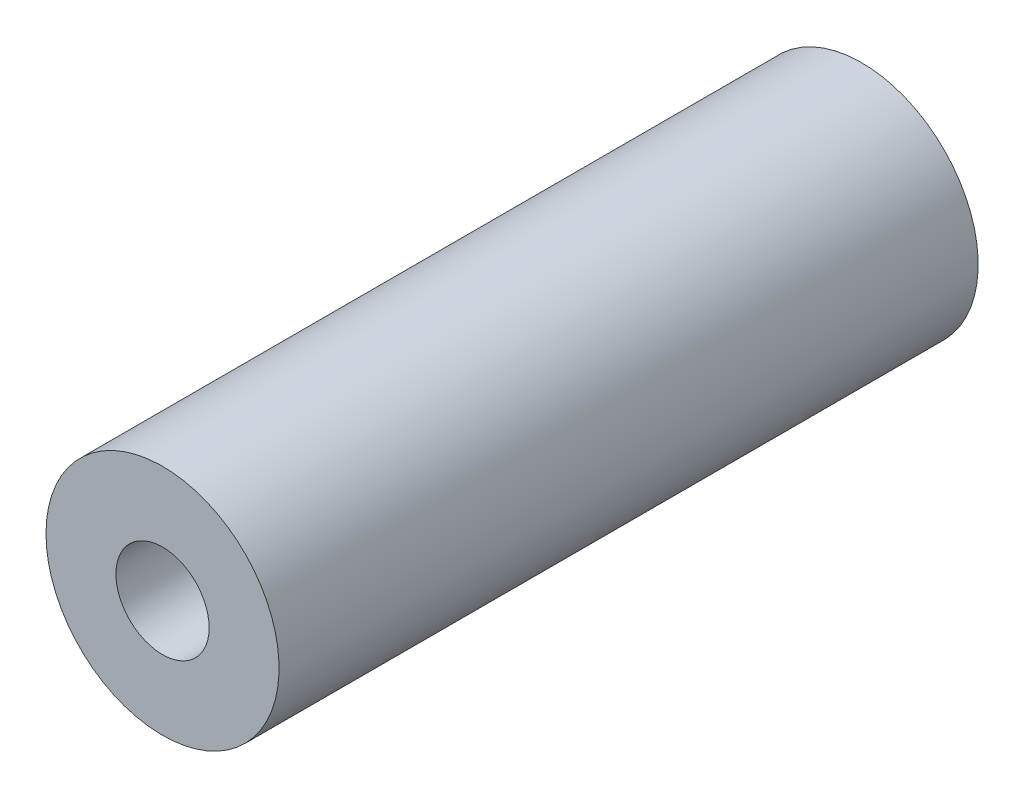
SolidWorks part; units mm, degrees
ref_plane "Front Plane" through (0, 0, 0) normal (0, 0, 1) x (1, 0, 0)
ref_plane "Top Plane" through (0, 0, 0) normal (0, 1, 0) x (1, 0, 0)
ref_plane "Right Plane" through (0, 0, 0) normal (1, 0, 0) x (0, 0, -1)
sketch "Sketch1" plane through (0, 0, 0) normal (0, 0, 1) x (1, 0, 0)
  circle A0 centre (0, 0) radius 12.7
extrude "Boss-Extrude1" add sketch "Sketch1" along normal blind 76.2
sketch "Sketch2" plane through (0, 0, 76.2) normal (0, 0, 1) x (1, 0, 0)
  circle A0 centre (0, 0) radius 5.08
extrude "Cut-Extrude1" cut sketch "Sketch2" against normal blind 12.7
sketch "Sketch3" plane through (0, 0, 76.2) normal (0, 0, 1) x (1, 0, 0)
  circle A0 centre (0, 0) radius 1.778
